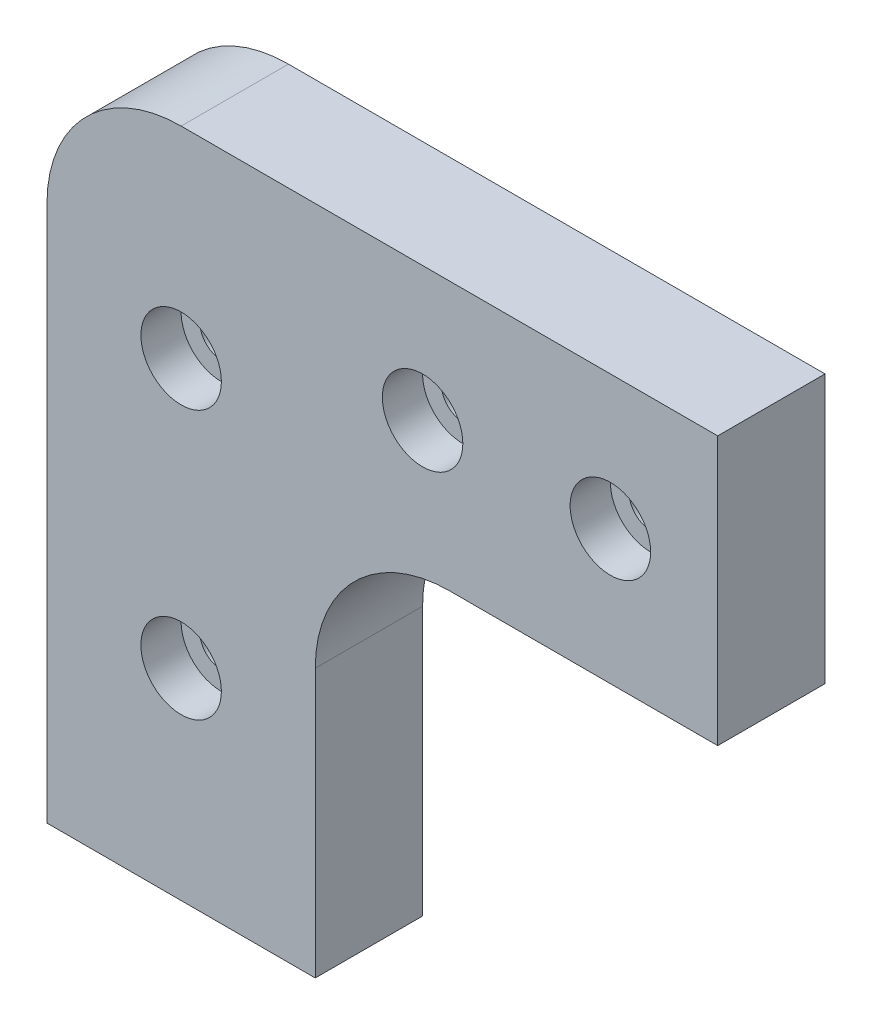
SolidWorks part; units mm, degrees
ref_plane "前视基准面" through (0, 0, 0) normal (0, 0, 1) x (1, 0, 0)
ref_plane "上视基准面" through (0, 0, 0) normal (0, 1, 0) x (1, 0, 0)
ref_plane "右视基准面" through (0, 0, 0) normal (1, 0, 0) x (0, 0, -1)
other "Configuration Table"
sketch "草图1" plane through (0, 0, 0) normal (0, 0, 1) x (1, 0, 0)
  line L0 (-10, 77.5) -> (-10, -160) construction
  line L2 (10, 57.5) -> (10, 27.5)
  line L3 (10, 27.5) -> (-10, 27.5)
  line L4 (-10, 77.5) -> (-10, 27.5)
  line L5 (-10, 77.5) -> (40, 77.5)
  line L7 (10, 57.5) -> (40, 57.5)
  line L8 (40, 77.5) -> (40, 57.5)
  line L9 (184.3942, 77.5) -> (10.0042, 77.5) construction
  line L10 (184.3942, 57.5) -> (10.0042, 57.5) construction
  line L11 (10, -130.0288) -> (10, 47.5288) construction
  circle A0 centre (32, 67.5) radius 1.6
  circle A1 centre (18, 67.5) radius 1.6
  circle A2 centre (0, 62.5) radius 1.6
  circle A3 centre (0, 42.5) radius 1.6
  point P22 (0, 27.5)
  point P23 (40, 67.5)
  dimension "D2" = 3.2
  dimension "D1" = 50
  dimension "D3" = 8
  dimension "D4" = 8
  dimension "D5" = 15
  dimension "D6" = 15
extrude "凸台-拉伸1" add sketch "草图1" along normal blind 8
sketch "草图2" plane through (0, 0, 8) normal (0, 0, 1) x (1, 0, 0)
  circle A0 centre (32, 67.5) radius 3
  circle A1 centre (0, 42.5) radius 1.6
  circle A2 centre (0, 42.5) radius 1.6 construction
  circle A3 centre (0, 62.5) radius 1.6
  circle A4 centre (0, 62.5) radius 1.6 construction
  circle A5 centre (18, 67.5) radius 1.6
  circle A6 centre (18, 67.5) radius 1.6 construction
  circle A7 centre (32, 67.5) radius 1.6
  circle A8 centre (32, 67.5) radius 1.6 construction
  circle A9 centre (18, 67.5) radius 3
  circle A10 centre (0, 62.5) radius 3
  circle A11 centre (0, 42.5) radius 3
  dimension "D1" = 6
  dimension "D2" = 0
  dimension "D3" = 0
  dimension "D4" = 0
  dimension "D5" = 0
extrude "切除-拉伸1" cut sketch "草图2" against normal blind 3
fillet "圆角1" radius 10 2 edges at (10, 57.5, 4) (-10, 77.5, 4)
